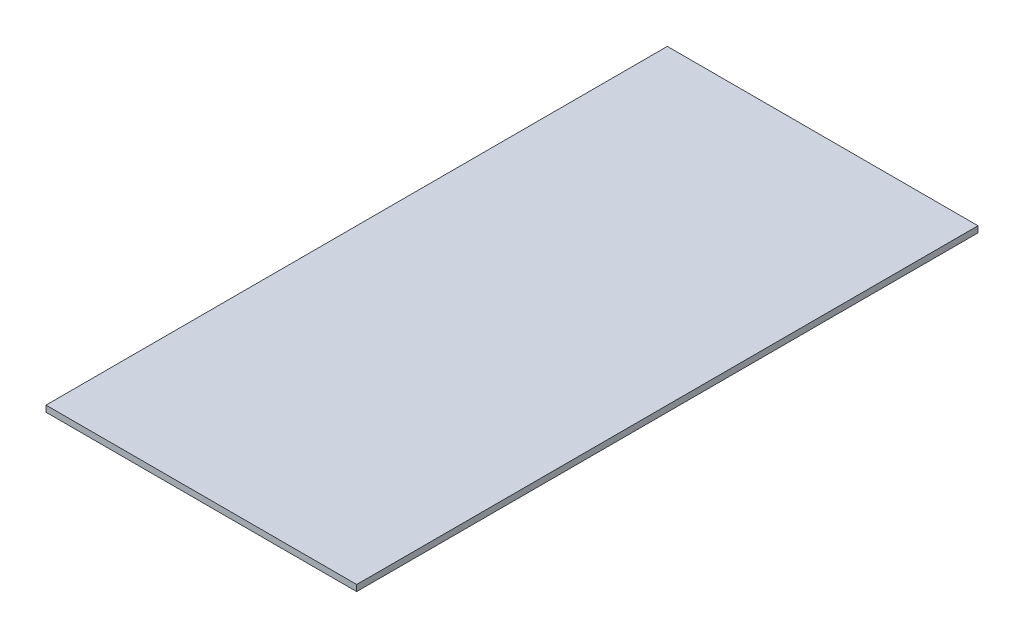
SolidWorks part; units mm, degrees
ref_plane "Front Plane" through (0, 0, 0) normal (0, 0, 1) x (1, 0, 0)
ref_plane "Top Plane" through (0, 0, 0) normal (0, 1, 0) x (1, 0, 0)
ref_plane "Right Plane" through (0, 0, 0) normal (1, 0, 0) x (0, 0, -1)
sketch "Sketch1" plane through (0, 0, 0) normal (0, 1, 0) x (1, 0, 0)
  line L1 (-457.2, -914.4) -> (457.2, -914.4)
  line L2 (-457.2, -914.4) -> (-457.2, 914.4)
  line L3 (-457.2, 914.4) -> (457.2, 914.4)
  line L4 (457.2, -914.4) -> (457.2, 914.4)
  line L5 (-457.2, -914.4) -> (457.2, 914.4) construction
  line L6 (-457.2, 914.4) -> (457.2, -914.4) construction
  point P0 (0, 0)
  dimension "D1" = 1828.8
  dimension "D2" = 914.4
extrude "Boss-Extrude1" add sketch "Sketch1" along normal blind 18.2562
